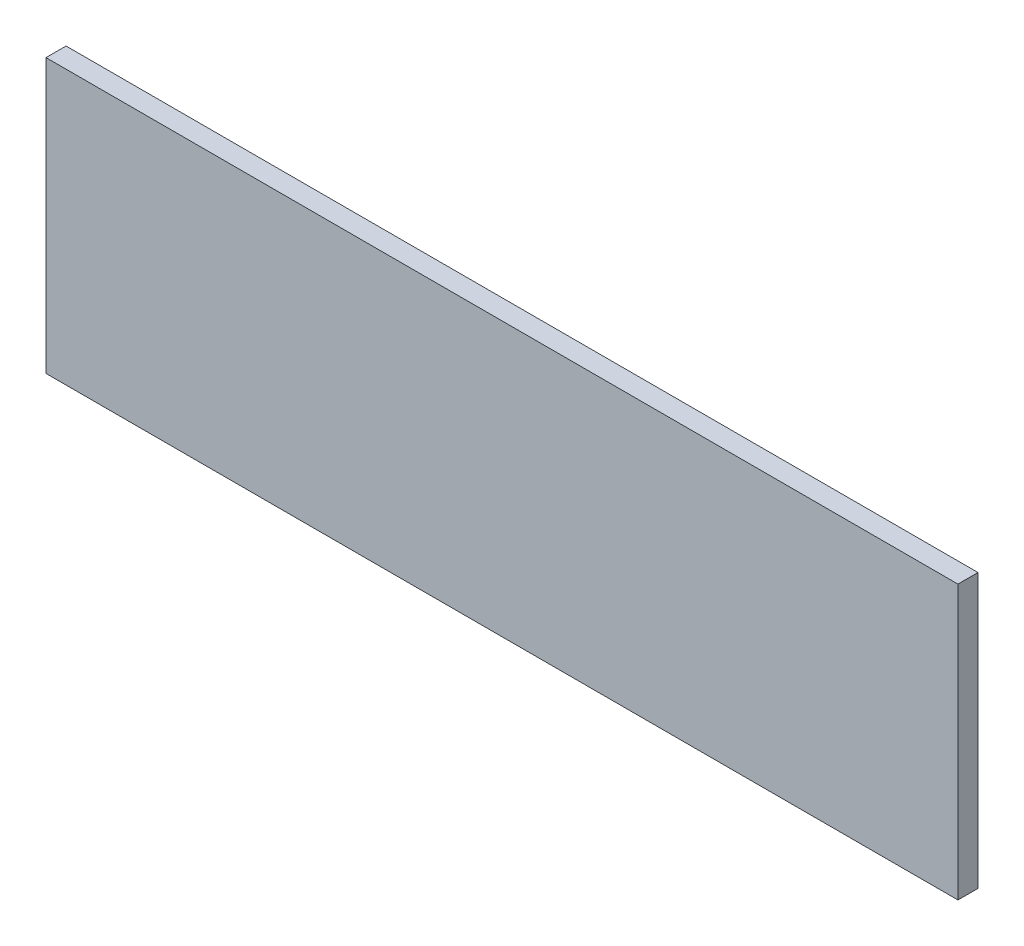
SolidWorks part; units mm, degrees
ref_plane "Front Plane" through (0, 0, 0) normal (0, 0, 1) x (1, 0, 0)
ref_plane "Top Plane" through (0, 0, 0) normal (0, 1, 0) x (1, 0, 0)
ref_plane "Right Plane" through (0, 0, 0) normal (1, 0, 0) x (0, 0, -1)
sketch "Sketch1" plane through (0, 0, 0) normal (0, 0, 1) x (1, 0, 0)
  line L1 (-127, -38.1) -> (127, -38.1)
  line L2 (-127, -38.1) -> (-127, 38.1)
  line L3 (-127, 38.1) -> (127, 38.1)
  line L4 (127, -38.1) -> (127, 38.1)
  line L5 (-127, -38.1) -> (127, 38.1) construction
  line L6 (-127, 38.1) -> (127, -38.1) construction
  point P0 (0, 0)
  dimension "D1" = 254
  dimension "D2" = 76.2
extrude "Boss-Extrude1" add sketch "Sketch1" along normal blind 5.588
